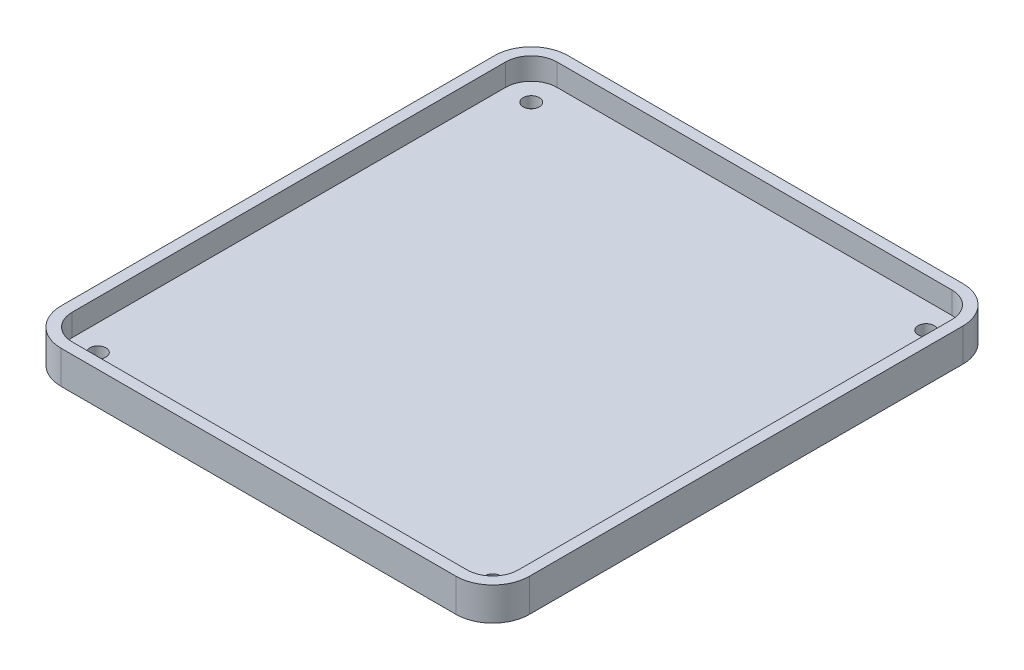
SolidWorks part; units mm, degrees
ref_plane "前视基准面" through (0, 0, 0) normal (0, 0, 1) x (1, 0, 0)
ref_plane "上视基准面" through (0, 0, 0) normal (0, 1, 0) x (1, 0, 0)
ref_plane "右视基准面" through (0, 0, 0) normal (1, 0, 0) x (0, 0, -1)
other "Configuration Table"
sketch "草图1" plane through (0, 0, 0) normal (0, 1, 0) x (1, 0, 0)
  line L1 (10, 0) -> (117.5, 0)
  line L2 (0, 10) -> (0, 128)
  line L3 (10, 138) -> (117.5, 138)
  line L4 (127.5, 10) -> (127.5, 128)
  arc A0 (10, 138) -> (0, 128) centre (10, 128) ccw
  arc A1 (117.5, 0) -> (127.5, 10) centre (117.5, 10) ccw
  arc A2 (127.5, 128) -> (117.5, 138) centre (117.5, 128) ccw
  arc A3 (10, 0) -> (0, 10) centre (10, 10) cw
  point P7 (0, 138)
  point P10 (127.5, 0)
  point P15 (0, 0)
  dimension "D3" = 10
  dimension "D4" = 10
  dimension "D1" = 127.5
  dimension "D2" = 138
extrude "凸台-拉伸1" add sketch "草图1" along normal blind 3
sketch "草图2" plane through (0, 3, 0) normal (0, 1, 0) x (1, 0, 0)
  line L0 (117.5, 135) -> (10, 135)
  line L1 (3, 128) -> (3, 10)
  line L2 (10, 3) -> (117.5, 3)
  line L3 (124.5, 10) -> (124.5, 128)
  line L4 (0, 128) -> (0, 10)
  line L5 (10, 0) -> (117.5, 0)
  line L6 (127.5, 10) -> (127.5, 128)
  line L7 (117.5, 138) -> (10, 138)
  line L8 (0, 128) -> (0, 10)
  line L9 (10, 0) -> (117.5, 0)
  line L10 (127.5, 10) -> (127.5, 128)
  line L11 (117.5, 138) -> (10, 138)
  arc A0 (10, 135) -> (3, 128) centre (10, 128) ccw
  arc A1 (3, 10) -> (10, 3) centre (10, 10) ccw
  arc A2 (117.5, 3) -> (124.5, 10) centre (117.5, 10) ccw
  arc A3 (124.5, 128) -> (117.5, 135) centre (117.5, 128) ccw
  arc A4 (10, 138) -> (0, 128) centre (10, 128) ccw
  arc A5 (0, 10) -> (10, 0) centre (10, 10) ccw
  arc A6 (117.5, 0) -> (127.5, 10) centre (117.5, 10) ccw
  arc A7 (127.5, 128) -> (117.5, 138) centre (117.5, 128) ccw
  arc A8 (10, 138) -> (0, 128) centre (10, 128) ccw
  arc A9 (0, 10) -> (10, 0) centre (10, 10) ccw
  arc A10 (117.5, 0) -> (127.5, 10) centre (117.5, 10) ccw
  arc A11 (127.5, 128) -> (117.5, 138) centre (117.5, 128) ccw
  dimension "D1" = 0
  dimension "D2" = 3
extrude "凸台-拉伸2" add sketch "草图2" along normal blind 6
sketch "草图3" plane through (0, 3, 0) normal (0, 1, 0) x (1, 0, 0)
  line L8 (10, 128) -> (10, 10)
  line L9 (10, 10) -> (117.5, 10)
  line L10 (117.5, 10) -> (117.5, 128)
  line L11 (117.5, 128) -> (10, 128)
  line L12 (10, 128) -> (10, 10) construction
  line L13 (10, 10) -> (117.5, 10) construction
  line L14 (117.5, 10) -> (117.5, 128) construction
  line L15 (117.5, 128) -> (10, 128) construction
  circle A0 centre (10, 128) radius 2.2
  circle A1 centre (117.5, 128) radius 2.2
  circle A2 centre (10, 10) radius 2.2
  circle A3 centre (117.5, 10) radius 2.2
  point P0 (9.8231, 10)
  point P8 (10, 127.7021)
  dimension "D1" = 4.4
  dimension "D2" = 10
extrude "切除-拉伸1" cut sketch "草图3" against normal through all
